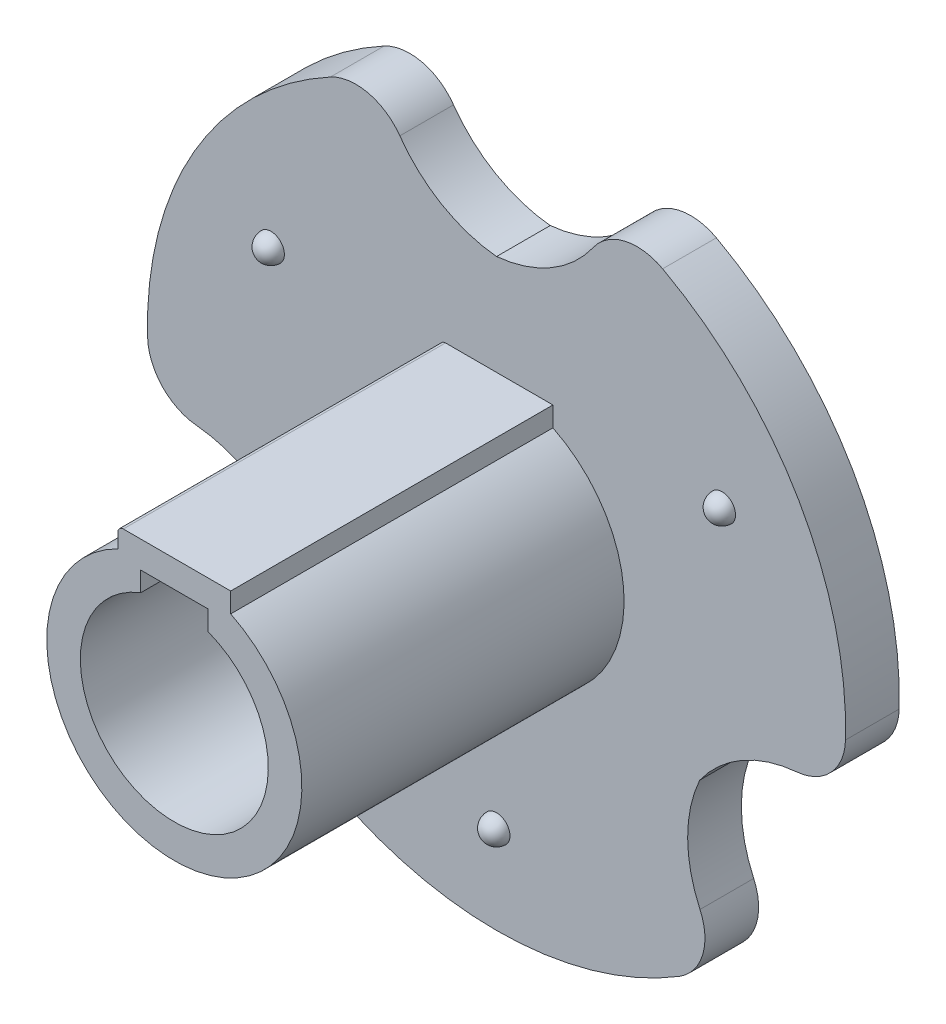
SolidWorks part; units mm, degrees
ref_plane "Front Plane" through (0, 0, 0) normal (0, 0, 1) x (1, 0, 0)
ref_plane "Top Plane" through (0, 0, 0) normal (0, 1, 0) x (1, 0, 0)
ref_plane "Right Plane" through (0, 0, 0) normal (1, 0, 0) x (0, 0, -1)
sketch "Esquisse1" plane through (0, 0, 0) normal (0, 0, 1) x (1, 0, 0)
  line L1 (-1.25, 4) -> (1.25, 4)
  line L2 (-1.25, 4) -> (-1.25, 3.2692)
  line L4 (1.25, 4) -> (1.25, 3.2692)
  line L5 (-2.1, 5) -> (2.1, 5)
  line L6 (-2.1, 5) -> (-2.1, 4.2606)
  line L8 (2.1, 5) -> (2.1, 4.2606)
  arc A0 (-1.25, 3.2692) -> (1.25, 3.2692) centre (0, 0) ccw
  arc A1 (-2.1, 4.2606) -> (2.1, 4.2606) centre (0, 0) ccw
  dimension "D1" = 7
  dimension "D4" = 9.5
  dimension "D2" = 2.5
  dimension "D3" = 4
  dimension "D5" = 4.2
  dimension "D6" = 5
extrude "Boss.-Extru.1" add sketch "Esquisse1" along normal blind 12
sketch "Esquisse3" plane through (0, 0, 0) normal (0, 0, -1) x (-1, 0, 0)
  circle A0 centre (0, 0) radius 13
  dimension "D1" = 26
extrude "Boss.-Extru.5" add sketch "Esquisse3" along normal blind 2
sketch "Esquisse4" plane through (0, 0, -2) normal (0, 0, -1) x (-1, 0, 0)
  circle A0 centre (0, 0) radius 6
  circle A2 centre (0, 0) radius 4.75
  dimension "D1" = 12
  dimension "D2" = 9.5
extrude "Boss.-Extru.6" add sketch "Esquisse4" along normal blind 1.1
sketch "Esquisse5" plane through (0, 0, 0) normal (0, 0, 1) x (1, 0, 0)
  line L0 (1.25, 4) -> (-1.25, 4) construction
  line L1 (1.25, 4) -> (-1.25, 4)
  line L2 (-1.25, 4) -> (-1.25, 3.2692) construction
  line L3 (-1.25, 4) -> (-1.25, 3.2692)
  line L4 (1.25, 3.2692) -> (1.25, 4) construction
  line L5 (1.25, 3.2692) -> (1.25, 4)
  arc A0 (-1.25, 3.2692) -> (1.25, 3.2692) centre (0, 0) ccw construction
  arc A1 (-1.25, 3.2692) -> (1.25, 3.2692) centre (0, 0) ccw
extrude "Enlèv. mat.-Extru.2" cut sketch "Esquisse5" against normal up to next
fillet "Congé1" radius 0.5 1 edges at (-6, 0, -3.1)
fillet "Congé2" radius 0.5 1 edges at (-4.75, 0, -3.1)
sketch "Esquisse6" plane through (0, 0, -2) normal (0, 0, -1) x (-1, 0, 0)
  line L0 (0, 0) -> (0, 17.9368) construction
  line L1 (0, 0) -> (13.4977, -7.7929) construction
  line L2 (0, 0) -> (-18.1482, -10.4779) construction
  arc A0 (3.6011, 10.8285) -> (0, 8.7366) centre (-0.4828, 13.7132) cw
  circle A2 centre (0, 0) radius 11.2 construction
  arc A3 (-3.6011, 10.8285) -> (0, 8.7366) centre (0.4828, 13.7132) ccw
  arc A12 (-6.1864, 11.4336) -> (-3.6011, 10.8285) centre (-5.2347, 9.6746) cw
  arc A13 (6.1864, 11.4336) -> (-6.1864, 11.4336) centre (0, 0) ccw
  circle A14 centre (0, 0) radius 13 construction
  circle A15 centre (0, 0) radius 13 construction
  arc A16 (6.1864, 11.4336) -> (3.6011, 10.8285) centre (5.2347, 9.6746) ccw
  dimension "D3" = 22.4
  dimension "D4" = 10
  dimension "D2" = 120
extrude "Enlèv. mat.-Extru.3" cut sketch "Esquisse6" against normal up to next
sketch "Esquisse7" plane through (0, 0, 0) normal (0, 0, 1) x (1, 0, 0)
  line L0 (0, 0) -> (0, -15.1186) construction
  line L1 (0, 0) -> (15.0818, 7.4992) construction
  line L3 (-0.4953, -9.6319) -> (0.4953, -9.7681)
  arc A0 (0.4953, -9.7681) -> (-0.4953, -9.6319) centre (0, -9.7) ccw
  dimension "D4" = 0.5
  dimension "D3" = 9.7
revolve "Révolution2" add sketch "Esquisse7" angle 360 about L3
pattern_circular "Répétition circulaire1" count 2 over 120 about axis through (0, 0, 0) along (0, 0, -1) of "Révolution2"
pattern_circular "Répétition circulaire2" count 2 every 240 about axis through (0, 0, 0) along (0, 0, -1) of "Révolution2"
fillet "Congé3" radius 0.2 1 edges at (-2.1, 5, 6)
pattern_circular "Répétition circulaire3" count 2 over 240 about axis through (0, 0, 0) along (0, 0, 1) of "Enlèv. mat.-Extru.3"
pattern_circular "Répétition circulaire4" count 2 over 120 about axis through (0, 0, 0) along (0, 0, 1) of "Enlèv. mat.-Extru.3"
